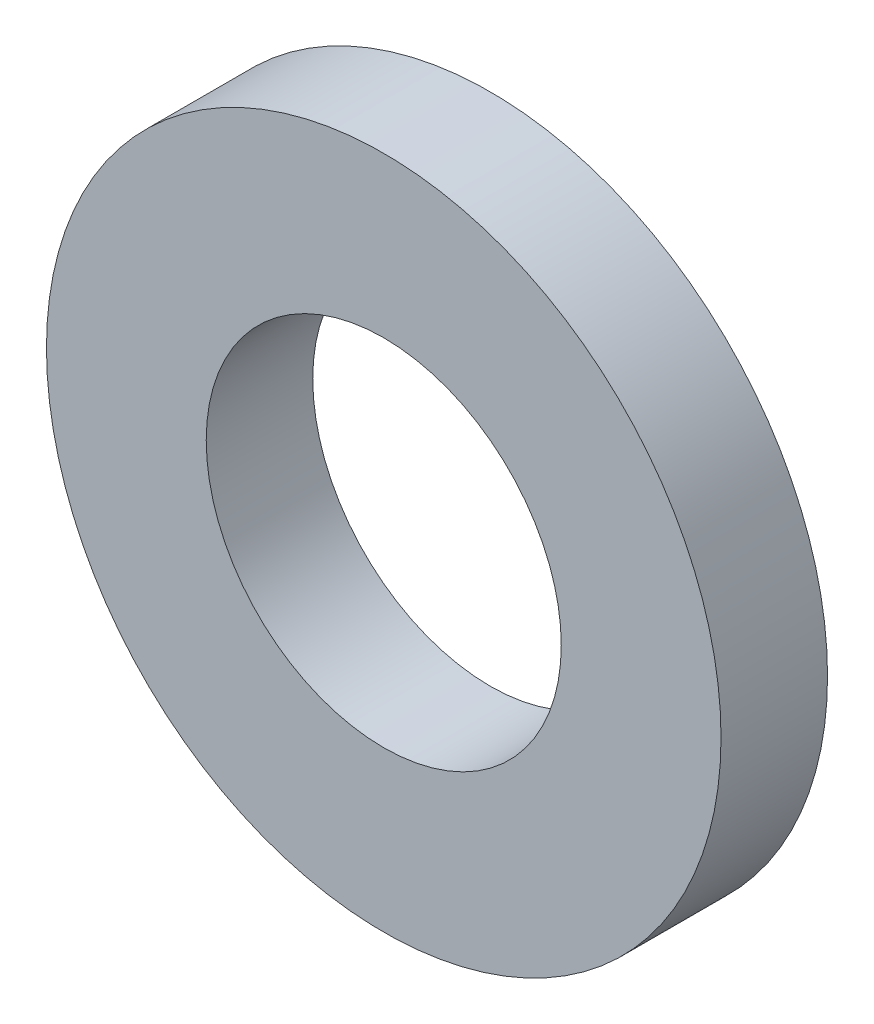
SolidWorks part; units mm, degrees
ref_plane "Front Plane" through (0, 0, 0) normal (0, 0, 1) x (1, 0, 0)
ref_plane "Top Plane" through (0, 0, 0) normal (0, 1, 0) x (1, 0, 0)
ref_plane "Right Plane" through (0, 0, 0) normal (1, 0, 0) x (0, 0, -1)
sketch "Sketch1" plane through (0, 0, 0) normal (0, 0, 1) x (1, 0, 0)
  circle A0 centre (0, 0) radius 9.5
  circle A1 centre (0, 0) radius 5
  dimension "D1" = 19
  dimension "D2" = 10
extrude "Boss-Extrude1" add sketch "Sketch1" along normal mid plane 3
